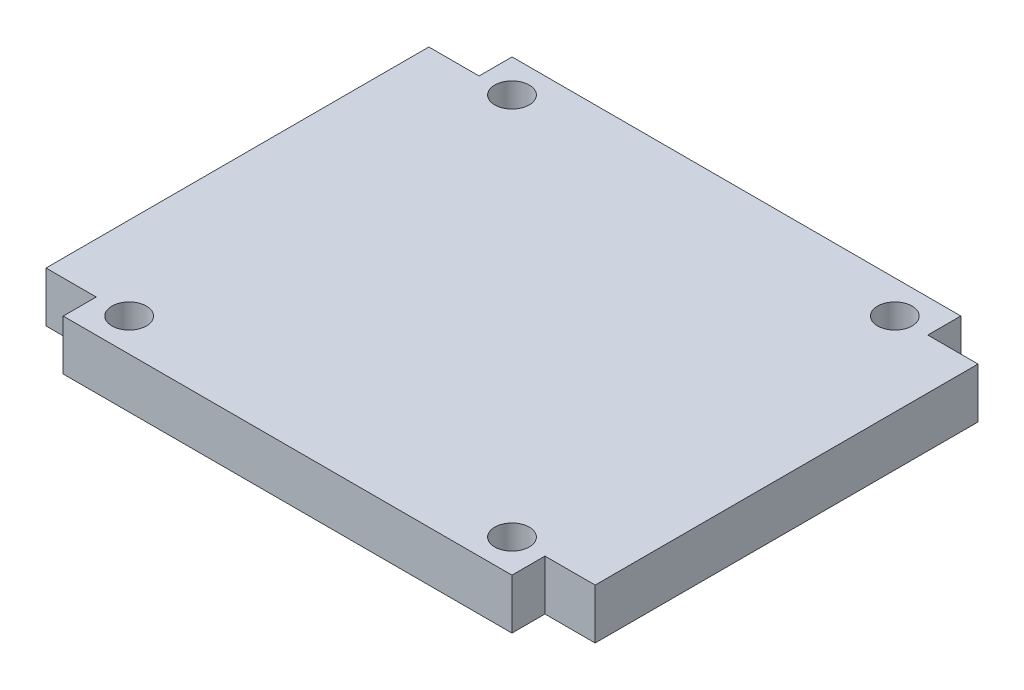
SolidWorks part; units mm, degrees
ref_plane "Front Plane" through (0, 0, 0) normal (0, 0, 1) x (1, 0, 0)
ref_plane "Top Plane" through (0, 0, 0) normal (0, 1, 0) x (1, 0, 0)
ref_plane "Right Plane" through (0, 0, 0) normal (1, 0, 0) x (0, 0, -1)
sketch "Sketch1" plane through (0, 0, 0) normal (0, 1, 0) x (1, 0, 0)
  line L0 (-15.25, 15.25) -> (15.25, 15.25) construction
  line L1 (-15.25, 15.25) -> (-15.25, -15.25) construction
  circle A0 centre (-15.25, 15.25) radius 1.375
  circle A1 centre (15.25, 15.25) radius 1.375
  circle A2 centre (15.25, -15.25) radius 1.375
  circle A3 centre (-15.25, -15.25) radius 1.375
  point P10 (0, 15.25)
  point P12 (-15.25, 0)
  dimension "D1" = 2.75
  dimension "D2" = 30.5
  dimension "D3" = 30.5
sketch "Sketch2" plane through (0, 0, 0) normal (0, 1, 0) x (1, 0, 0)
  line L0 (17.875, 15.25) -> (21.875, 15.25)
  line L1 (17.875, -15.25) -> (21.875, -15.25)
  line L2 (-17.875, -17.88) -> (17.875, -17.88)
  line L3 (-17.875, -17.88) -> (-17.875, -15.25)
  line L4 (-17.875, 17.88) -> (17.875, 17.88)
  line L5 (17.875, -17.88) -> (17.875, -15.25)
  line L6 (-17.875, -17.88) -> (17.875, 17.88) construction
  line L7 (-17.875, 17.88) -> (17.875, -17.88) construction
  line L8 (21.875, 15.25) -> (21.875, -15.25)
  line L9 (17.875, 15.25) -> (17.875, 17.88)
  line L10 (0, 12.9542) -> (0, -12.1546) construction
  line L11 (-17.875, -15.25) -> (-21.875, -15.25)
  line L12 (-21.875, 15.25) -> (-21.875, -15.25)
  line L13 (-17.875, 15.25) -> (-21.875, 15.25)
  line L14 (-17.875, 15.25) -> (-17.875, 17.88)
  circle A1 centre (15.25, 15.25) radius 1.375 construction
  point P4 (0, 0)
  dimension "D1" = 2.625
  dimension "D2" = 2.63
  dimension "D3" = 4
extrude "Boss-Extrude1" add sketch "Sketch2" along normal blind 4
extrude "Cut-Extrude1" cut sketch "Sketch1" along normal blind 4
